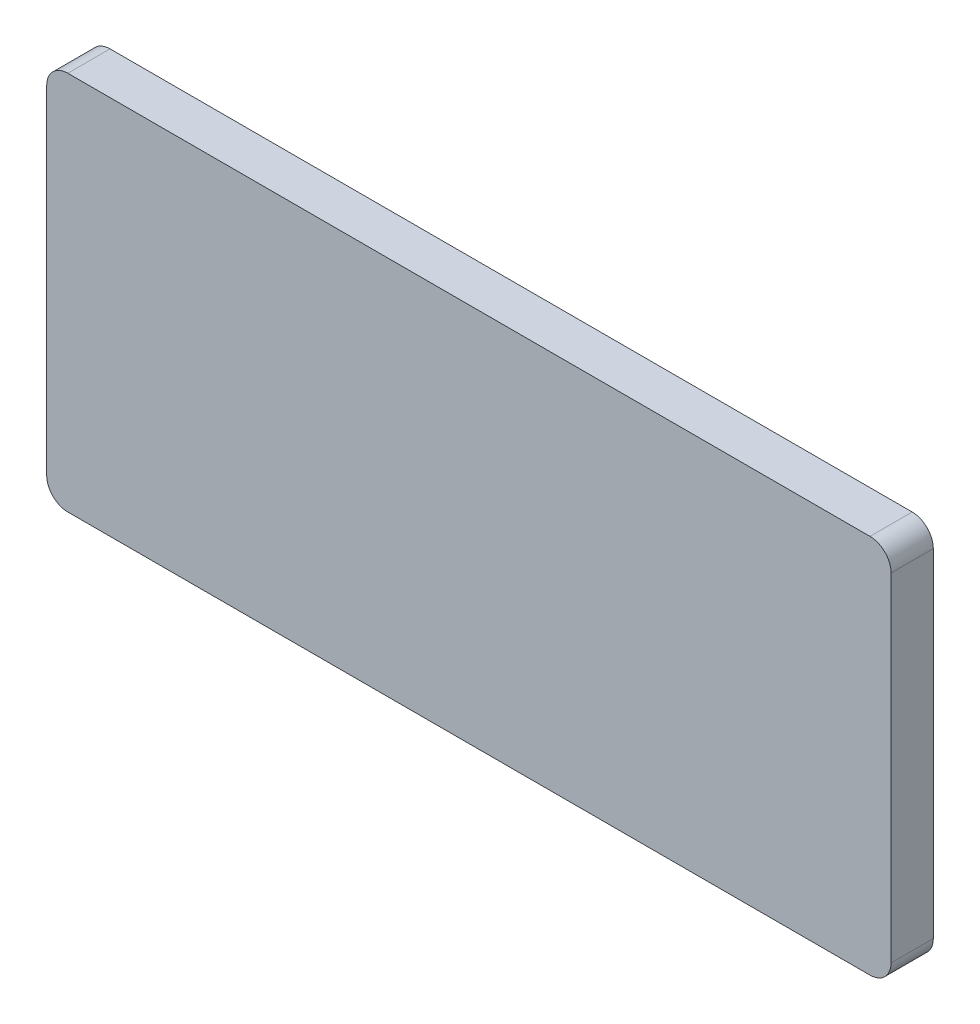
SolidWorks part; units mm, degrees
material "AISI 1020"
ref_plane "Front Plane" through (0, 0, 0) normal (0, 0, 1) x (1, 0, 0)
ref_plane "Top Plane" through (0, 0, 0) normal (0, 1, 0) x (1, 0, 0)
ref_plane "Right Plane" through (0, 0, 0) normal (1, 0, 0) x (0, 0, -1)
sketch "Sketch1" plane through (0, 0, 0) normal (0, 0, 1) x (1, 0, 0)
  line L1 (-254, -114.3) -> (254, -114.3)
  line L2 (-254, -114.3) -> (-254, 114.3)
  line L3 (-254, 114.3) -> (254, 114.3)
  line L4 (254, -114.3) -> (254, 114.3)
  line L5 (-254, -114.3) -> (254, 114.3) construction
  line L6 (-254, 114.3) -> (254, -114.3) construction
  point P0 (0, 0)
  dimension "D1" = 508
  dimension "D2" = 228.6
extrude "Boss-Extrude1" add sketch "Sketch1" along normal blind 25.4 contours L3 L4 L1 L2
fillet "Fillet3" radius 12.7 1 edges at (254, 114.3, 12.7)
fillet "Fillet4" radius 12.7 3 edges at (-254, 114.3, 12.7) (-254, -114.3, 12.7) (254, -114.3, 12.7)
equation "\"A\"= 100"
equation "\"B\"= 100"
equation "\"C\"= 100"
equation "\"D\"= 100"
equation "\"E\"= 100"
